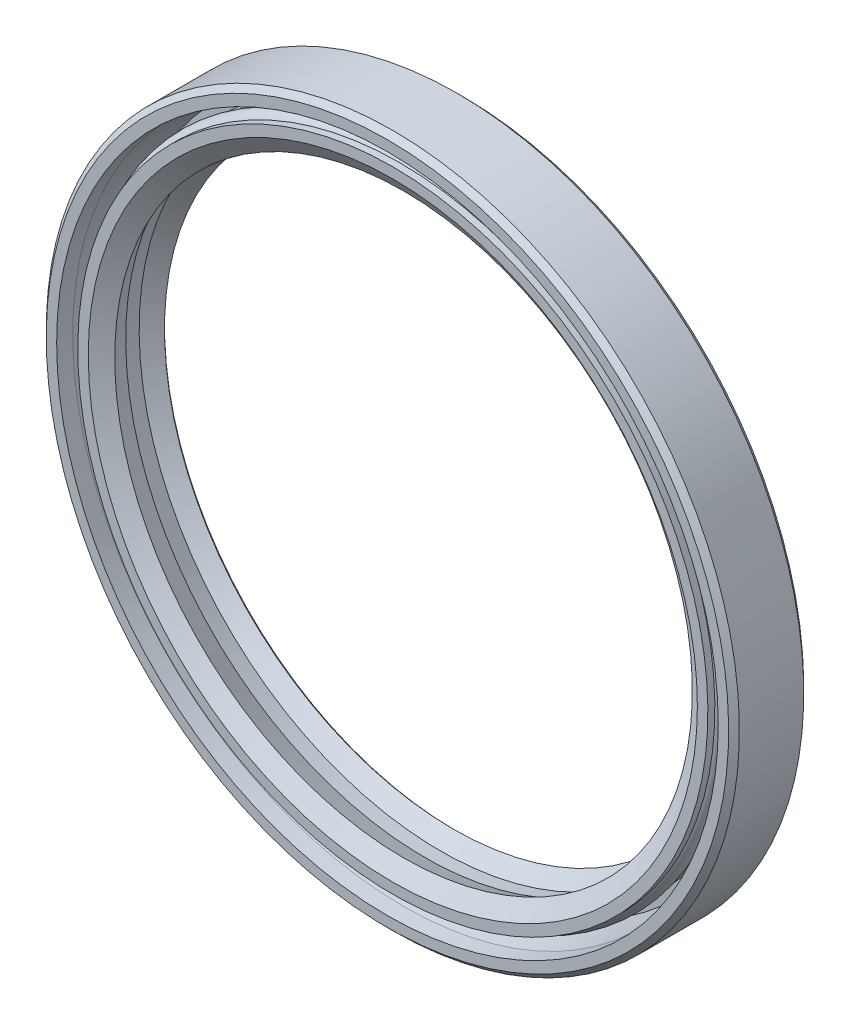
SolidWorks part; units mm, degrees
material "VITON"
ref_plane "정면" through (0, 0, 0) normal (0, 0, 1) x (1, 0, 0)
ref_plane "윗면" through (0, 0, 0) normal (0, 1, 0) x (1, 0, 0)
ref_plane "우측면" through (0, 0, 0) normal (1, 0, 0) x (0, 0, -1)
sketch "스케치1" plane through (0, 0, 0) normal (1, 0, 0) x (0, 0, -1)
  line L0 (0, 0) -> (-13, 0) construction
  line L1 (-10.2143, 57.2727) -> (-2.7857, 56.3636)
  line L2 (-13, 60) -> (0, 60) construction
  line L3 (-13, 60) -> (-13, 50) construction
  line L4 (-13, 50) -> (0, 50) construction
  line L5 (0, 60) -> (0, 50) construction
  line L6 (-12.0714, 60) -> (-0.9286, 60)
  line L7 (-13, 59.0714) -> (-13, 57.2727)
  line L8 (-13, 57.2727) -> (-10.2143, 57.2727)
  line L9 (0, 59.0714) -> (0, 52.7273)
  line L10 (-2.7857, 56.3636) -> (-2.7857, 54.5455)
  line L11 (-2.7857, 54.5455) -> (-7.7111, 54.5455)
  line L12 (-12.0714, 54.5455) -> (-12.0714, 52.7273)
  line L13 (-12.0714, 52.7273) -> (-10.2143, 50)
  line L14 (-10.2143, 50) -> (-6.5, 51.8182)
  line L15 (-6.5, 51.8182) -> (-3.796, 52.1964)
  line L16 (-12.0714, 60) -> (-13, 59.0714)
  line L17 (-0.9286, 60) -> (0, 59.0714)
  line L18 (-10.8603, 54.5455) -> (-12.0714, 54.5455)
  line L19 (-13, -50) -> (0, -50) construction
  line L20 (-13, -60) -> (0, -60) construction
  line L21 (0, -60) -> (0, -50) construction
  line L22 (-13, -60) -> (-13, -50) construction
  line L23 (-13, -50) -> (0, -60) construction
  line L24 (0, -50) -> (-13, -60) construction
  line L25 (-3.796, 52.1964) -> (-1.5997, 50)
  line L26 (-1.5997, 50) -> (-1.1818, 50.4178)
  line L27 (-1.1818, 50.4178) -> (-1.9244, 52.4581)
  line L28 (-1.9244, 52.4581) -> (0, 52.7273)
  circle A0 centre (-9.2857, 53.6364) radius 1.8182 construction
  arc A1 (-10.8603, 54.5455) -> (-7.7111, 54.5455) centre (-9.2857, 53.6364) cw
  point P8 (-13, 60)
  point P11 (0, 60)
  dimension "D14" = 3.6364
  dimension "D7" = 2.7857
  dimension "D8" = 2.7273
  dimension "D10" = 2.7857
  dimension "D11" = 3.6364
  dimension "D12" = 3.7143
  dimension "D13" = 0.9286
  dimension "D15" = 2.7857
  dimension "D16" = 2.7857
  dimension "D18" = 0.9091
  dimension "D20" = 1.8182
  dimension "D9" = 0.9091
  dimension "D5" = 0.9091
  dimension "D6" = 1.1818
  dimension "D17" = 45
  dimension "D19" = 25
  dimension "D21" = 0.5909
revolve "회전1" add sketch "스케치1" angle 360 about L0
equation "\"D3@스케치1\"= \"B\" * ( 0.50 / 7 )"
equation "\"D4@스케치1\"= \"B\" * ( 0.50 / 7 )"
equation "\"D12@스케치1\"= \"B\" * ( 2 / 7 )"
equation "\"D10@스케치1\"= \"B\" * ( 1.50 / 7 )"
equation "\"D7@스케치1\"= \"B\" * ( 1.50 / 7 )"
equation "\"D11@스케치1\" = ( ( \"OD\" - \"ID\" ) / 2 ) * ( 2 / 5.5 )"
equation "\"D8@스케치1\"= ( ( \"OD\" - \"ID\" ) / 2 ) * ( 1.5 / 5.5 )"
equation "\"D9@스케치1\"= ( ( \"OD\" - \"ID\" ) / 2 ) * ( 0.5 / 5.5 )"
equation "\"D20@스케치1\"= ( ( \"OD\" - \"ID\" ) / 2 ) * ( 1 / 5.5 )"
equation "\"D18@스케치1\"= ( ( \"OD\" - \"ID\" ) / 2 ) * ( 0.5 / 5.5 )"
equation "\"D5@스케치1\"= ( ( \"OD\" - \"ID\" ) / 2 ) * ( 0.5 / 5.5 )"
equation "\"D13@스케치1\"= \"B\" * ( 0.5 / 7 )"
equation "\"D16@스케치1\"= \"B\" * ( 1.50 / 7 )"
equation "\"D15@스케치1\"= \"B\" * ( 1.50 / 7 )"
equation "\"D14@스케치1\"= ( ( \"OD\" - \"ID\" ) / 2 ) * ( 2 / 5.5 )"
equation "\"D6@스케치1\" = \"B\" * ( 1 / 11 )"
equation "\"D21@스케치1\"= \"B\" * ( 0.50 / 11 )"
equation "\"Mass\"= \"SW-질량\" / 1000"
